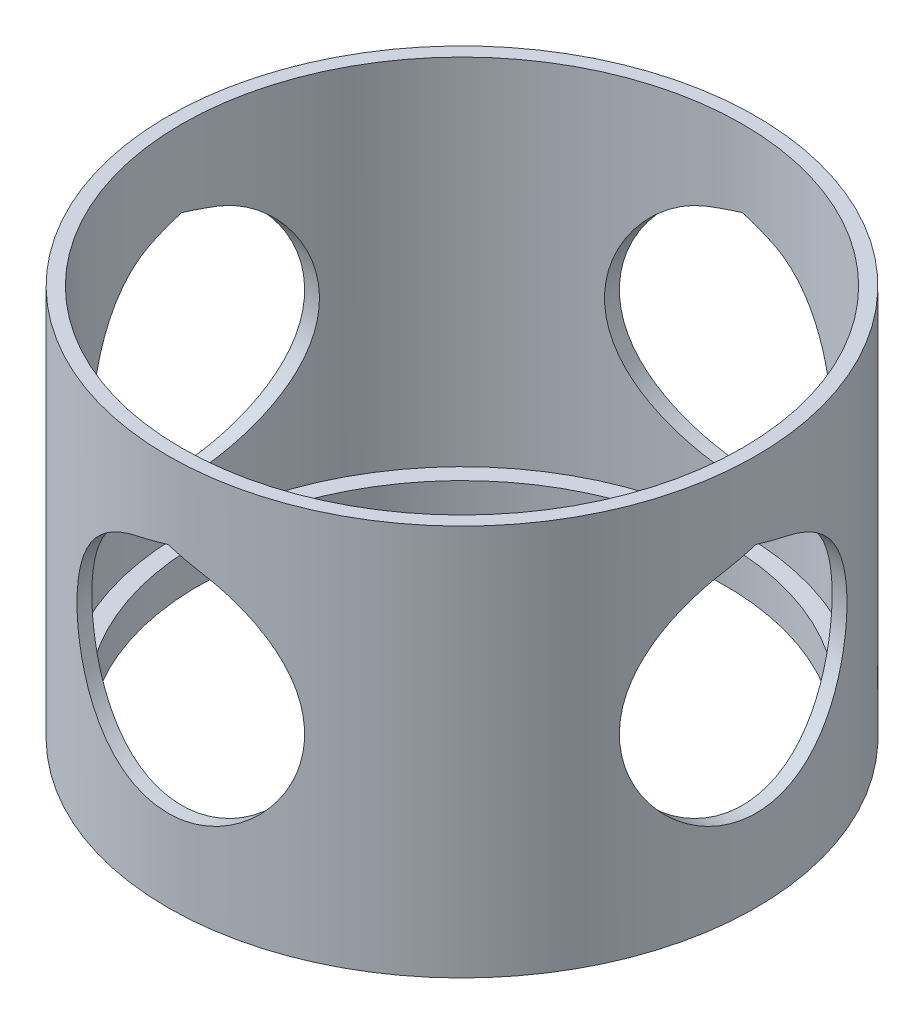
SolidWorks part; units mm, degrees
ref_plane "Front Plane" through (0, 0, 0) normal (0, 0, 1) x (1, 0, 0)
ref_plane "Top Plane" through (0, 0, 0) normal (0, 1, 0) x (1, 0, 0)
ref_plane "Right Plane" through (0, 0, 0) normal (1, 0, 0) x (0, 0, -1)
sketch "Sketch1" plane through (0, 0, 0) normal (0, 1, 0) x (1, 0, 0)
  circle A0 centre (0, 0) radius 43.9039
  circle A1 centre (0, 0) radius 41.8719
  dimension "D1" = 87.8078
  dimension "D2" = 2.032
extrude "Boss-Extrude1" add sketch "Sketch1" along normal blind 58.42
sketch "Sketch2" plane through (0, 0, 0) normal (0, 0, 1) x (1, 0, 0)
  line L0 (0, 0) -> (0, 58.42) construction
  line L1 (41.8719, 58.42) -> (-41.8719, 58.42) construction
  line L2 (-43.9039, 29.21) -> (43.9039, 29.21) construction
  line L3 (-43.9039, 58.42) -> (-43.9039, 0) construction
  line L4 (43.9039, 0) -> (43.9039, 58.42) construction
  line L5 (-4.9248, 45.4733) -> (0, 46.9646)
  line L6 (0, 46.9646) -> (4.9248, 45.4733)
  line L7 (0, 46.2026) -> (0, 46.9646)
  circle A0 centre (0, 29.21) radius 16.9926
  dimension "D1" = 33.9852
  dimension "D2" = 0.762
extrude "Cut-Extrude2" cut sketch "Sketch2" against normal blind 56.896 contours A0 L7 L5 | A0 L6 L7 | A0
pattern_circular "CirPattern3" count 4 every 90 about axis through (0, 0, 0) along (0, 1, 0) of "Cut-Extrude2"
sketch "Sketch6" plane through (0, 58.42, 0) normal (0, 1, 0) x (1, 0, 0)
  line L0 (-20.8364, 36.2462) -> (-35.6327, 21.8689)
  line L1 (-36.2462, -20.8364) -> (-21.8689, -35.6327)
  line L2 (20.8364, -36.2462) -> (35.6327, -21.8689)
  line L3 (36.2462, 20.8364) -> (21.8689, 35.6327)
  line L5 (-29.0576, -28.2346) -> (0, 0) construction
  line L6 (-20.8364, 36.2462) -> (-35.6327, 21.8689)
  line L7 (-36.2462, -20.8364) -> (-21.8689, -35.6327)
  line L8 (20.8364, -36.2462) -> (35.6327, -21.8689)
  line L9 (36.2462, 20.8364) -> (21.8689, 35.6327)
  circle A0 centre (0, 0) radius 43.9039
  arc A1 (21.8689, 35.6327) -> (-20.8364, 36.2462) centre (0, 0) ccw
  arc A2 (-35.6327, 21.8689) -> (-36.2462, -20.8364) centre (0, 0) ccw
  arc A3 (-21.8689, -35.6327) -> (20.8364, -36.2462) centre (0, 0) ccw
  arc A4 (35.6327, -21.8689) -> (36.2462, 20.8364) centre (0, 0) ccw
  circle A5 centre (0, 0) radius 43.9039
  arc A6 (21.8689, 35.6327) -> (-20.8364, 36.2462) centre (0, 0) ccw
  arc A7 (-35.6327, 21.8689) -> (-36.2462, -20.8364) centre (0, 0) ccw
  arc A8 (-21.8689, -35.6327) -> (20.8364, -36.2462) centre (0, 0) ccw
  arc A9 (35.6327, -21.8689) -> (36.2462, 20.8364) centre (0, 0) ccw
ref_plane "Plane1" through (0, 0, 0) normal (0.6969, 0, 0.7172) x (0.7172, 0, -0.6969)
sketch "Sketch9" plane through (0, 0, 0) normal (0.6969, 0, 0.7172) x (0.7172, 0, -0.6969)
  line L0 (-43.8268, 0) -> (-27.9176, 0)
  line L1 (-37.6512, 5.4568) -> (-43.8268, 5.4568)
  line L2 (-37.6512, 5.4568) -> (-37.6512, 11.8576)
  line L3 (-37.6512, 11.8576) -> (-43.8268, 11.8576)
  line L4 (-43.8268, 5.4568) -> (-43.8268, 11.8576)
  line L5 (-43.9039, 0) -> (43.9039, 0) construction
  point P6 (-43.8268, 0)
ref_plane "Plane2" through (31.4875, 0, -30.5956) normal (0.7172, 0, -0.6969) x (-0.6969, 0, -0.7172)
sketch "Sketch10" plane through (31.4875, 0, -30.5956) normal (0.7172, 0, -0.6969) x (-0.6969, 0, -0.7172)
  line L0 (0, 5.4568) -> (0, 11.8576) construction
  line L1 (0, 5.4568) -> (0, 11.8576)
  circle A0 centre (0, 8.6572) radius 0.8001
sketch "Sketch11" plane through (31.4875, 0, -30.5956) normal (0.7172, 0, -0.6969) x (-0.6969, 0, -0.7172)
  line L0 (0, 5.4568) -> (0, 11.8576) construction
  line L1 (0, 10.1368) -> (0, 10.3908)
  line L2 (0.771, 9.92) -> (0, 10.3908)
  line L3 (0, 10.3908) -> (-0.771, 9.92)
  circle A0 centre (0, 8.6572) radius 1.4796
  dimension "D1" = 2.9591
  dimension "D2" = 0.254
extrude "Cut-Extrude3" cut sketch "Sketch11" against normal up to next contours A0 L1 L3 | A0 L2 L1 | A0
pattern_circular "CirPattern4" count 2 every 180 about axis through (0, 58.42, 0) along (0, -1, 0) of "Cut-Extrude3"
fillet "Fillet1" radius 0.127 6 edges at (-31.7549, 10.1554, 30.318) (-31.2176, 10.1554, 30.8709) (-31.3789, 7.1859, 30.7069) (31.7549, 10.1554, -30.318) (31.2176, 10.1554, -30.8709) (31.3789, 7.1859, -30.7069)
sketch "Sketch13" plane through (31.4875, 0, -30.5956) normal (0.7172, 0, -0.6969) x (-0.6969, 0, -0.7172)
  circle A0 centre (0, 8.6572) radius 1.7363
  dimension "D1" = 3.4725
ref_plane "Plane3" through (0, 5.4568, 0) normal (0, -1, 0) x (-1, 0, 0)
sketch "Sketch14" plane through (0, 5.4568, 0) normal (0, -1, 0) x (-1, 0, 0)
  circle A0 centre (0, 0) radius 41.8719
  circle A1 centre (0, 0) radius 39.3319
  circle A2 centre (0, 0) radius 41.8719 construction
  dimension "D1" = 2.54
extrude "Boss-Extrude2" add sketch "Sketch14" along normal up to surface (5.4568 mm away)
